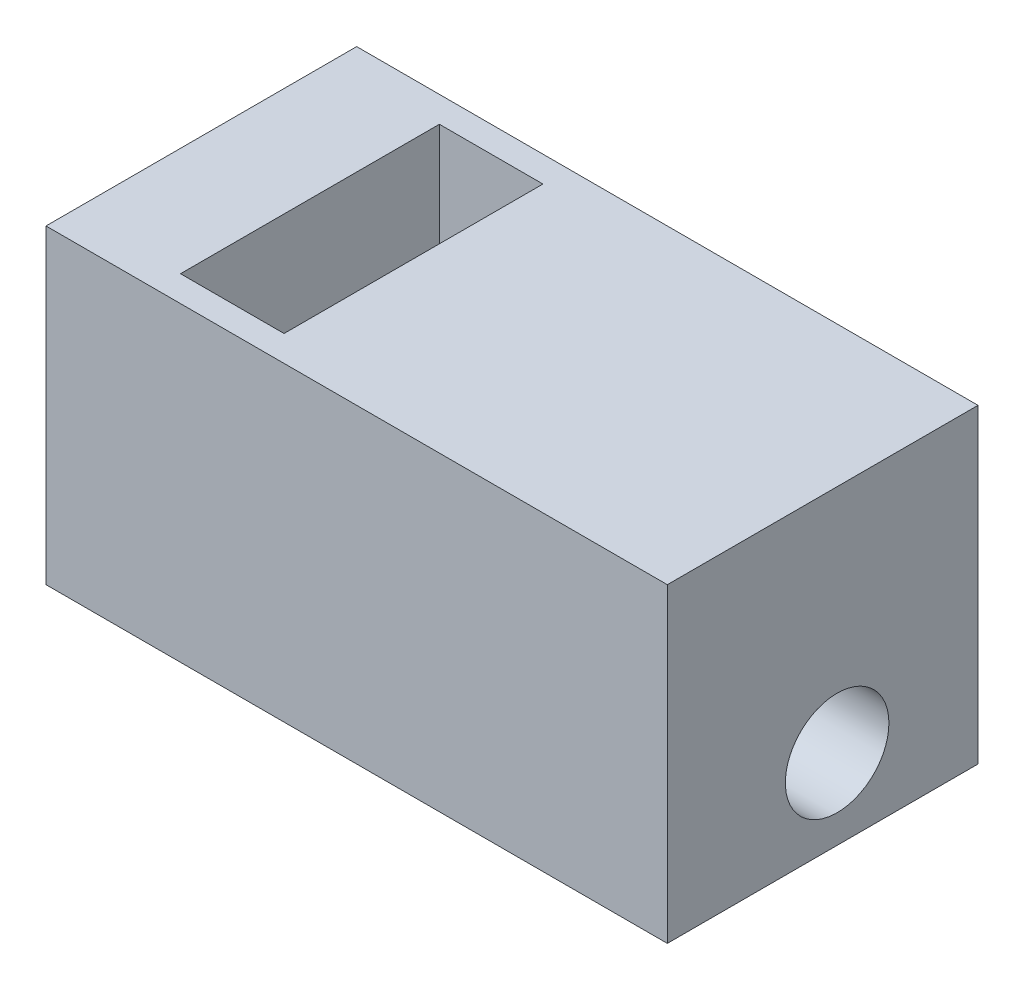
SolidWorks part; units mm, degrees
ref_plane "Front Plane" through (0, 0, 0) normal (0, 0, 1) x (1, 0, 0)
ref_plane "Top Plane" through (0, 0, 0) normal (0, 1, 0) x (1, 0, 0)
ref_plane "Right Plane" through (0, 0, 0) normal (1, 0, 0) x (0, 0, -1)
sketch "Sketch1" plane through (0, 0, 0) normal (0, 1, 0) x (1, 0, 0)
  line L1 (-62.7474, 36.0304) -> (89.6526, 36.0304)
  line L2 (-62.7474, 36.0304) -> (-62.7474, -40.1696)
  line L3 (-62.7474, -40.1696) -> (89.6526, -40.1696)
  line L4 (89.6526, 36.0304) -> (89.6526, -40.1696)
  dimension "D1" = 76.2
  dimension "D2" = 152.4
extrude "Boss-Extrude1" add sketch "Sketch1" along normal blind 76.2
sketch "Sketch2" plane through (89.6526, 0, 0) normal (1, 0, 0) x (0, 0, -1)
  circle A0 centre (1.4782, 19.6328) radius 12.7
  point P2 (7.4616, 20.8394)
  point P3 (1.4782, 19.6328)
extrude "Cut-Extrude1" cut sketch "Sketch2" against normal through all
sketch "Sketch3" plane through (0, 76.2, 0) normal (0, 1, 0) x (1, 0, 0)
  line L0 (89.6526, 36.0304) -> (-62.7474, 36.0304) construction
  line L1 (-36.1071, 29.6804) -> (-10.7071, 29.6804)
  line L2 (-36.1071, 29.6804) -> (-36.1071, -33.8196)
  line L3 (-36.1071, -33.8196) -> (-10.7071, -33.8196)
  line L4 (-10.7071, 29.6804) -> (-10.7071, -33.8196)
  point P4 (-23.4071, 29.6804)
  dimension "D1" = 25.4
  dimension "D2" = 63.5
  dimension "D3" = 6.35
extrude "Cut-Extrude2" cut sketch "Sketch3" against normal blind 25.4
